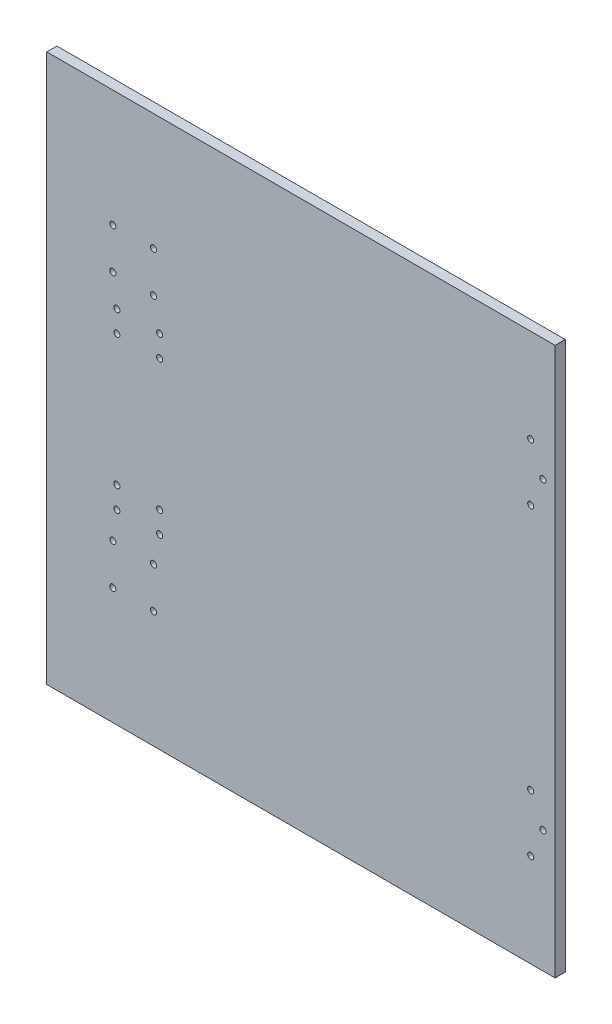
SolidWorks part; units mm, degrees
ref_plane "Plan de face" through (0, 0, 0) normal (0, 0, 1) x (1, 0, 0)
ref_plane "Plan de dessus" through (0, 0, 0) normal (0, 1, 0) x (1, 0, 0)
ref_plane "Plan de droite" through (0, 0, 0) normal (1, 0, 0) x (0, 0, -1)
sketch "Esquisse1" plane through (0, 0, 0) normal (0, 0, 1) x (1, 0, 0)
  line L1 (-125, 134.715) -> (125, 134.715)
  line L2 (-125, 134.715) -> (-125, -134.715)
  line L3 (-125, -134.715) -> (125, -134.715)
  line L4 (125, 134.715) -> (125, -134.715)
  line L5 (-125, 134.715) -> (125, -134.715) construction
  line L6 (-125, -134.715) -> (125, 134.715) construction
  point P0 (0, 0)
  dimension "D1" = 250
  dimension "D2" = 269.43
extrude "Boss.-Extru.1" add sketch "Esquisse1" along normal blind 5
sketch "Esquisse3" plane through (0, 0, 0) normal (0, 0, -1) x (-1, 0, 0)
  circle A0 centre (72.5, 77.215) radius 1.5
  circle A1 centre (92.5, 77.215) radius 1.5
  circle A2 centre (92.5, 57.215) radius 1.5
  circle A3 centre (72.5, 57.215) radius 1.5
  circle A4 centre (72.5, -57.215) radius 1.5
  circle A5 centre (92.5, -57.215) radius 1.5
  circle A6 centre (72.5, -77.215) radius 1.5
  circle A7 centre (92.5, -77.215) radius 1.5
  circle A8 centre (-113, 88.715) radius 1.5
  circle A9 centre (-119, 74.715) radius 1.5
  circle A10 centre (-113, 60.715) radius 1.5
  circle A11 centre (-113, -60.715) radius 1.5
  circle A12 centre (-119, -74.715) radius 1.5
  circle A13 centre (-113, -88.715) radius 1.5
extrude "Enlèv. mat.-Extru.2" cut sketch "Esquisse3" against normal through all
sketch "Esquisse4" plane through (0, 0, 5) normal (0, 0, 1) x (1, 0, 0)
  circle A0 centre (-69.4721, -43.0489) radius 1.5
  circle A1 centre (-69.4721, -32.5211) radius 1.5
  circle A2 centre (-90.5279, -43.0489) radius 1.5
  circle A3 centre (-90.5279, -32.5211) radius 1.5
  circle A4 centre (-69.4721, 31.9511) radius 1.5
  circle A5 centre (-90.5279, 31.9511) radius 1.5
  circle A6 centre (-69.4721, 42.4789) radius 1.5
  circle A7 centre (-90.5279, 42.4789) radius 1.5
extrude "Enlèv. mat.-Extru.3" cut sketch "Esquisse4" against normal through all
